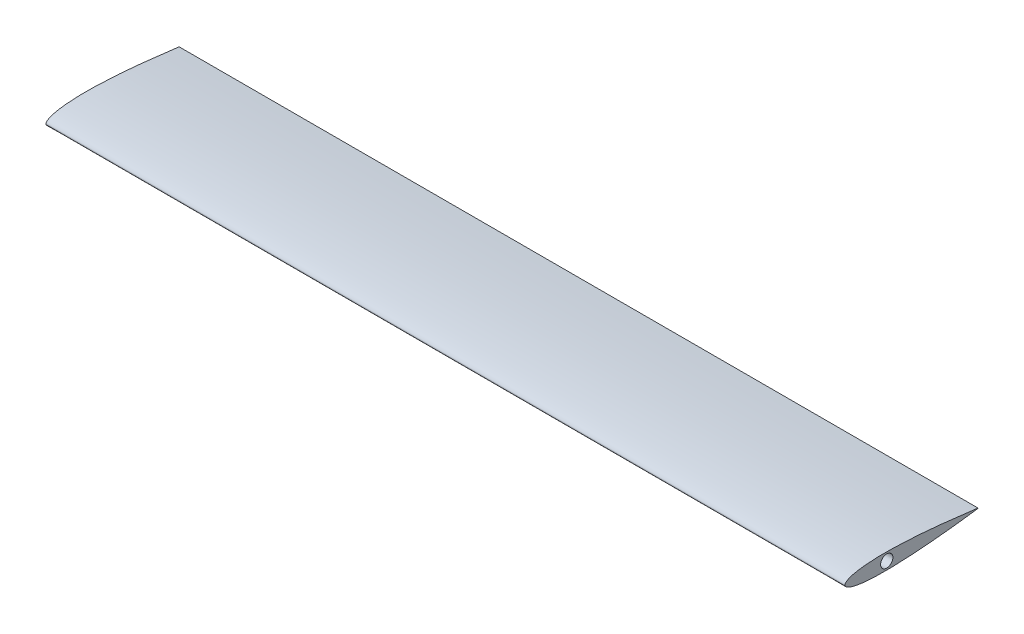
SolidWorks part; units mm, degrees
ref_plane "Ön Düzlem" through (0, 0, 0) normal (0, 0, 1) x (1, 0, 0)
ref_plane "Üst Düzlem" through (0, 0, 0) normal (0, 1, 0) x (1, 0, 0)
ref_plane "Sağ Düzlem" through (0, 0, 0) normal (1, 0, 0) x (0, 0, -1)
sketch "Sketch1" plane through (0, 0, 0) normal (1, 0, 0) x (0, 0, -1)
  line L0 (305.5, 117) -> (1527.5, 117) construction
  line L1 (124.9958, 7.6975) -> (124.9958, 7.3551)
  spline S0 degree 3 poles (124.9958, 7.6975) (121.5494, 8.133) (115.7079, 8.8711) (106.6128, 10.0012) (98.7767, 10.9001) (91.0104, 11.7181) (84.4662, 12.3744) (77.1231, 13.0109) (70.0969, 13.6616) (63.2322, 14.0383) (56.9512, 14.4586) (50.1831, 14.7448) (43.7131, 14.9288) (38.0167, 14.9868) (31.8671, 14.9642) (25.9611, 14.7642) (20.4185, 14.3189) (16.0809, 13.9021) (11.9484, 13.2767) (7.872, 12.4387) (4.5515, 11.4816) (1.9351, 10.1896) (0.4198, 8.8678) (-0.1163, 7.6764) (0.2285, 6.5757) (1.0921, 5.3828) (3.1213, 4.1827) (5.8339, 3.1224) (8.9694, 2.338) (12.4549, 1.6356) (16.398, 1.0576) (20.4074, 0.6193) (24.9405, 0.3185) (28.9969, 0.0979) (33.6404, 0.065) (37.6198, -0.0088) (42.1302, 0.0152) (46.8255, 0.1281) (52.0592, 0.3082) (57.5703, 0.566) (63.0666, 0.9035) (68.7816, 1.2736) (74.2411, 1.7012) (79.3321, 2.132) (83.7651, 2.5258) (88.3339, 3.015) (93.4519, 3.4955) (98.4485, 4.0307) (103.3599, 4.5597) (107.5347, 5.0511) (112.036, 5.6526) (116.8989, 6.2051) (121.1853, 6.8982) (124.0349, 7.1356) (124.8716, 7.3267) (124.9958, 7.3551) knots 0 0 0 0 0.04091 0.069341 0.107932 0.133796 0.161307 0.185386 0.220598 0.244394 0.266344 0.294731 0.324163 0.342565 0.361816 0.396586 0.412117 0.427295 0.447896 0.461301 0.476285 0.488528 0.495262 0.499816 0.502761 0.50837 0.516837 0.529992 0.542689 0.554812 0.57187 0.589596 0.602296 0.625369 0.637421 0.656977 0.672241 0.690534 0.712285 0.733913 0.755504 0.777134 0.801357 0.819993 0.837304 0.853767 0.874103 0.897841 0.912946 0.932278 0.947342 0.966429 0.989896 0.9985 1 1 1 1
extrude "Boss-Extrude1" add sketch "Sketch1" along normal blind 750
sketch "Sketch3" plane through (0, 0, 0) normal (-1, 0, 0) x (0, 0, 1)
  line L0 (-124.9958, 7.5263) -> (5.059, 7.5263) construction
  line L1 (-124.9958, 7.3551) -> (-124.9958, 7.6975) construction
  line L2 (-39.3203, 0.0045) -> (-39.3203, 14.9691) construction
  circle A0 centre (-39.3203, 7.4868) radius 5.75
  spline S0 degree 3 poles (-124.9958, 7.6975) (-121.5494, 8.133) (-115.7079, 8.8711) (-106.6128, 10.0012) (-98.7767, 10.9001) (-91.0104, 11.7181) (-84.4662, 12.3744) (-77.1231, 13.0109) (-70.0969, 13.6616) (-63.2322, 14.0383) (-56.9512, 14.4586) (-50.1831, 14.7448) (-43.7131, 14.9288) (-38.0167, 14.9868) (-31.8671, 14.9642) (-25.9611, 14.7642) (-20.4185, 14.3189) (-16.0809, 13.9021) (-11.9484, 13.2767) (-7.872, 12.4387) (-4.5515, 11.4816) (-1.9351, 10.1896) (-0.4198, 8.8678) (0.1163, 7.6764) (-0.2285, 6.5757) (-1.0921, 5.3828) (-3.1213, 4.1827) (-5.8339, 3.1224) (-8.9694, 2.338) (-12.4549, 1.6356) (-16.398, 1.0576) (-20.4074, 0.6193) (-24.9405, 0.3185) (-28.9969, 0.0979) (-33.6404, 0.065) (-37.6198, -0.0088) (-42.1302, 0.0152) (-46.8255, 0.1281) (-52.0592, 0.3082) (-57.5703, 0.566) (-63.0666, 0.9035) (-68.7816, 1.2736) (-74.2411, 1.7012) (-79.3321, 2.132) (-83.7651, 2.5258) (-88.3339, 3.015) (-93.4519, 3.4955) (-98.4485, 4.0307) (-103.3599, 4.5597) (-107.5347, 5.0511) (-112.036, 5.6526) (-116.8989, 6.2051) (-121.1853, 6.8982) (-124.0349, 7.1356) (-124.8716, 7.3267) (-124.9958, 7.3551) knots 0 0 0 0 0.04091 0.069341 0.107932 0.133796 0.161307 0.185386 0.220598 0.244394 0.266344 0.294731 0.324163 0.342565 0.361816 0.396586 0.412117 0.427295 0.447896 0.461301 0.476285 0.488528 0.495262 0.499816 0.502761 0.50837 0.516837 0.529992 0.542689 0.554812 0.57187 0.589596 0.602296 0.625369 0.637421 0.656977 0.672241 0.690534 0.712285 0.733913 0.755504 0.777134 0.801357 0.819993 0.837304 0.853767 0.874103 0.897841 0.912946 0.932278 0.947342 0.966429 0.989896 0.9985 1 1 1 1 construction
  dimension "D1" = 11.5
extrude "Cut-Extrude1" cut sketch "Sketch3" against normal blind 804
